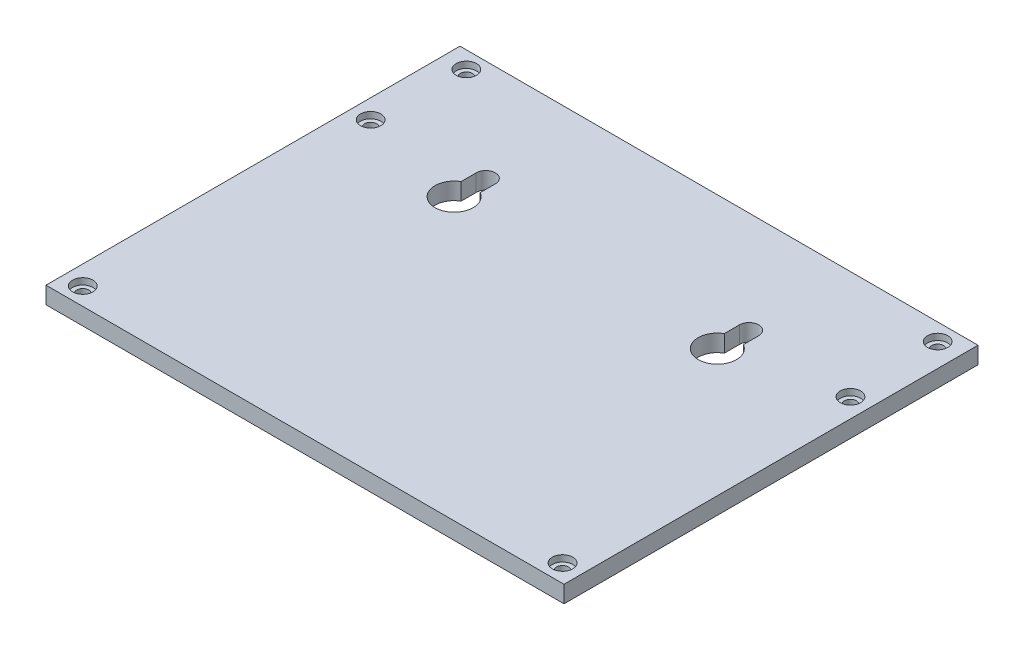
SolidWorks part; units mm, degrees
ref_plane "Front Plane" through (0, 0, 0) normal (0, 0, 1) x (1, 0, 0)
ref_plane "Top Plane" through (0, 0, 0) normal (0, 1, 0) x (1, 0, 0)
ref_plane "Right Plane" through (0, 0, 0) normal (1, 0, 0) x (0, 0, -1)
sketch "Sketch1" plane through (0, 0, 0) normal (0, 1, 0) x (1, 0, 0)
  line L1 (-91.4063, 40.0781) -> (30.5937, 40.0781)
  line L2 (-91.4063, 40.0781) -> (-91.4063, -57.4219)
  line L3 (-91.4063, -57.4219) -> (30.5938, -57.4219)
  line L4 (30.5937, 40.0781) -> (30.5938, -57.4219)
  dimension "D1" = 97.5
  dimension "D2" = 122
extrude "Boss-Extrude1" add sketch "Sketch1" along normal blind 4
sketch "Sketch2" plane through (0, 4, 0) normal (0, 1, 0) x (1, 0, 0)
  line L0 (-91.4063, 40.0781) -> (-91.4063, -57.4219) construction
  line L1 (30.5937, 40.0781) -> (-91.4063, 40.0781) construction
  line L2 (-91.4063, -57.4219) -> (30.5938, -57.4219) construction
  circle A0 centre (-86.9063, -53.2619) radius 1.4
  circle A1 centre (-86.9063, 14.5381) radius 1.4
  circle A2 centre (26.0938, 14.5381) radius 1.4
  circle A3 centre (26.0937, -53.2619) radius 1.4
  circle A4 centre (-85.9063, 36.0781) radius 1.4
  circle A5 centre (25.0938, 36.0781) radius 1.4
  point P8 (27.0937, 14.3781)
  point P9 (-85.9063, 14.3781)
  point P14 (-85.9063, 14.3781)
  dimension "D1" = 4.16
  dimension "D2" = 67.8
  dimension "D3" = 113
  dimension "D4" = 113
  dimension "D5" = 67.8
  dimension "D6" = 4.5
  dimension "D7" = 4.5
  dimension "D8" = 4.16
  dimension "D9" = 4
  dimension "D10" = 4
extrude "Cut-Extrude1" cut sketch "Sketch2" against normal blind 4
sketch "Sketch3" plane through (0, 4, 0) normal (0, 1, 0) x (1, 0, 0)
  circle A0 centre (-86.9063, 14.5381) radius 2.4
  circle A1 centre (-86.9063, -53.2619) radius 2.4
  circle A2 centre (26.0937, -53.2619) radius 2.4
  circle A3 centre (26.0938, 14.5381) radius 2.4
  circle A5 centre (-85.9063, 36.0781) radius 2.4
  circle A6 centre (25.0938, 36.0781) radius 2.4
  dimension "D1" = 4.8
  dimension "D2" = 4.8
  dimension "D3" = 4.8
  dimension "D4" = 4.8
  dimension "D5" = 4.8
  dimension "D6" = 4.8
extrude "Cut-Extrude2" cut sketch "Sketch3" against normal blind 1.5
sketch "Sketch4" plane through (0, 4, 0) normal (0, 1, 0) x (1, 0, 0)
  line L3 (-1.6563, 16.1573) -> (-1.6563, 12.5863)
  line L4 (-63.6563, 16.1573) -> (-63.6563, 12.5863)
  line L6 (-59.1563, 16.1573) -> (-59.1563, 12.5863)
  line L7 (2.8437, 16.1573) -> (2.8437, 12.5863)
  arc A2 (-59.1563, 12.5863) -> (-63.6563, 12.5863) centre (-61.4063, 8.6896) cw
  arc A4 (-63.6563, 16.1573) -> (-59.1563, 16.1573) centre (-61.4063, 16.1573) cw
  arc A7 (-1.6563, 16.1573) -> (2.8437, 16.1573) centre (0.5937, 16.1573) cw
  arc A8 (2.8437, 12.5863) -> (-1.6563, 12.5863) centre (0.5937, 8.6896) cw
  dimension "D1" = 2
  dimension "D3" = 4.5
extrude "Cut-Extrude3" cut sketch "Sketch4" against normal blind 4
